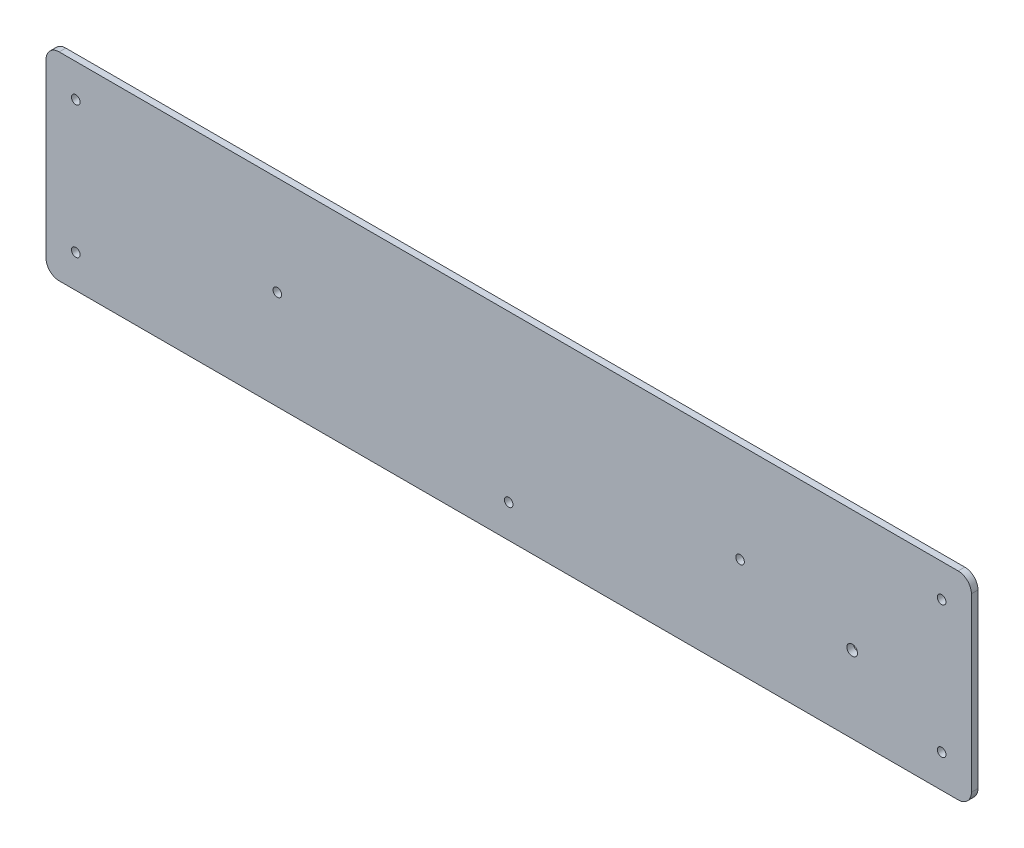
SolidWorks part; units mm, degrees
ref_plane "Front Plane" through (0, 0, 0) normal (0, 0, 1) x (1, 0, 0)
ref_plane "Top Plane" through (0, 0, 0) normal (0, 1, 0) x (1, 0, 0)
ref_plane "Right Plane" through (0, 0, 0) normal (1, 0, 0) x (0, 0, -1)
sketch "Sketch1" plane through (0, 0, 0) normal (0, 0, 1) x (1, 0, 0)
  line L1 (-350, 75) -> (350, 75)
  line L2 (-350, 75) -> (-350, -75)
  line L3 (-350, -75) -> (350, -75)
  line L4 (350, 75) -> (350, -75)
  line L5 (-350, 75) -> (350, -75) construction
  line L6 (-350, -75) -> (350, 75) construction
  point P0 (0, 0)
  dimension "D1" = 150
  dimension "D2" = 700
extrude "Boss-Extrude1" add sketch "Sketch1" along normal blind 5
fillet "Fillet1" radius 10 4 edges at (-350, -75, 2.5) (-350, 75, 2.5) (350, -75, 2.5) (350, 75, 2.5)
sketch "Sketch3" plane through (0, 0, 5) normal (0, 0, 1) x (1, 0, 0)
  circle A0 centre (0, -50) radius 3.25
  circle A1 centre (-327.4838, -50) radius 3.25
  circle A2 centre (327.4838, -50) radius 3.25
  circle A3 centre (-327.4838, 50) radius 3.25
  circle A4 centre (-175, 0) radius 3.25
  circle A5 centre (175, 0) radius 3.25
  circle A6 centre (327.4838, 50) radius 3.25
  dimension "D2" = 6.5
  dimension "D5" = 6.5
extrude "Cut-Extrude1" cut sketch "Sketch3" against normal blind 270
sketch "Sketch4" plane through (0, 0, 5) normal (0, 0, 1) x (1, 0, 0)
  line L0 (-340, -75) -> (340, -75) construction
  circle A0 centre (245.6592, -46.5) radius 4
  dimension "D1" = 28.5
extrude "Cut-Extrude2" cut sketch "Sketch4" against normal blind 10
sketch "Sketch5" plane through (0, 0, 5) normal (0, 0, 1) x (1, 0, 0)
  circle A0 centre (245.6592, -46.5) radius 4
extrude "Boss-Extrude2" add sketch "Sketch5" against normal blind 5
sketch "Sketch6" plane through (0, 0, 5) normal (0, 0, 1) x (1, 0, 0)
  circle A0 centre (259.8278, -16.9624) radius 4
extrude "Cut-Extrude3" cut sketch "Sketch6" against normal blind 20
